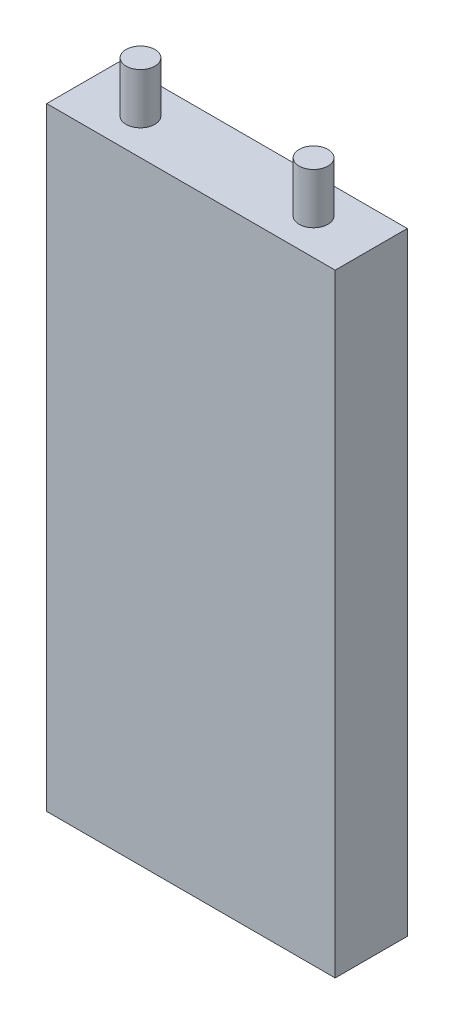
SolidWorks part; units mm, degrees
ref_plane "Front Plane" through (0, 0, 0) normal (0, 0, 1) x (1, 0, 0)
ref_plane "Top Plane" through (0, 0, 0) normal (0, 1, 0) x (1, 0, 0)
ref_plane "Right Plane" through (0, 0, 0) normal (1, 0, 0) x (0, 0, -1)
sketch "Sketch1" plane through (0, 0, 0) normal (0, 1, 0) x (1, 0, 0)
  line L0 (-25.4, 0) -> (76.2, 0)
  line L1 (-25.4, 0) -> (-25.4, 25.4)
  line L2 (-25.4, 25.4) -> (76.2, 25.4)
  line L3 (76.2, 25.4) -> (76.2, 0)
extrude "Boss-Extrude1" add sketch "Sketch1" along normal blind 215.9
sketch "Sketch3" plane through (0, 0, 0) normal (0, -1, 0) x (-1, 0, 0)
  line L0 (-25.4, 25.4) -> (-25.4, 0) construction
  line L1 (5.08, 12.7) -> (-25.4, 12.7) construction
  line L2 (-76.2, 25.4) -> (25.4, 25.4) construction
  line L3 (25.4, 0) -> (-76.2, 0) construction
  line L4 (-25.4, 12.7) -> (-55.88, 12.7) construction
  circle A0 centre (5.08, 12.7) radius 5.207
  circle A1 centre (-55.88, 12.7) radius 5.207
  dimension "D1" = 10.414
  dimension "D2" = 10.414
extrude "Cut-Extrude1" cut sketch "Sketch3" against normal blind 17.78
sketch "Sketch4" plane through (0, 215.9, 0) normal (0, 1, 0) x (1, 0, 0)
  line L0 (25.4, 25.4) -> (25.4, 0) construction
  line L1 (76.2, 25.4) -> (-25.4, 25.4) construction
  line L2 (-25.4, 0) -> (76.2, 0) construction
  line L3 (25.4, 12.7) -> (55.88, 12.7) construction
  line L4 (25.4, 12.7) -> (-5.08, 12.7) construction
  circle A0 centre (-5.08, 12.7) radius 5.08
  circle A1 centre (55.88, 12.7) radius 5.08
  dimension "D1" = 10.16
  dimension "D2" = 10.16
extrude "Boss-Extrude3" add sketch "Sketch4" along normal blind 17.78
